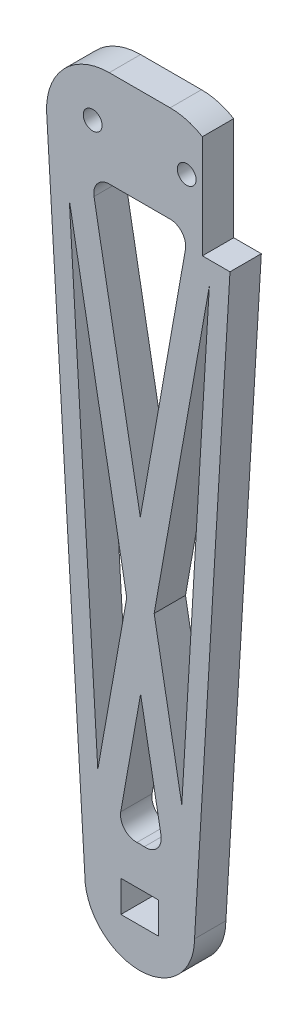
SolidWorks part; units mm, degrees
ref_plane "Front Plane" through (0, 0, 0) normal (0, 0, 1) x (1, 0, 0)
ref_plane "Top Plane" through (0, 0, 0) normal (0, 1, 0) x (1, 0, 0)
ref_plane "Right Plane" through (0, 0, 0) normal (1, 0, 0) x (0, 0, -1)
sketch "Sketch1" plane through (0, 0, 0) normal (0, 0, 1) x (1, 0, 0)
  line L0 (-30, 0) -> (30, 0)
  line L1 (0, 0) -> (15, 0)
  line L2 (55, 0) -> (-55, 0) construction
  line L3 (0, 0) -> (0, -210)
  line L4 (0, -44.7868) -> (0, 44.7868) construction
  line L5 (0, 0) -> (30, 0)
  line L6 (0, 0) -> (-30, 0)
  line L7 (0, 0) -> (-15, 0)
  line L8 (-6, -215) -> (6, -215)
  line L9 (-6, -215) -> (-6, -205)
  line L10 (-6, -205) -> (6, -205)
  line L11 (6, -215) -> (6, -205)
  line L12 (-6, -215) -> (6, -205) construction
  line L13 (-6, -205) -> (6, -215) construction
  line L14 (0, 0) -> (0, 15)
  line L15 (-30, 0) -> (-17.5, -210)
  line L16 (-30, 0) -> (30, 0)
  line L17 (-30, 0) -> (-30, 15.7704)
  line L18 (-30, 15.7704) -> (30, 15.7704)
  line L19 (30, 0) -> (30, 15.7704)
  line L20 (30, 0) -> (17.5, -210)
  circle A0 centre (15, 0) radius 3
  circle A1 centre (-15, 0) radius 3
  circle A2 centre (0, -210) radius 17.5
  point P4 (0, 0)
  dimension "D7" = 6
  dimension "D9" = 6
  dimension "D11" = 35
  dimension "D1" = 210
  dimension "D2" = 30
  dimension "D3" = 30
  dimension "D4" = 10
  dimension "D5" = 12
  dimension "D6" = 15
  dimension "D8" = 15
  dimension "D10" = 15
extrude "Boss-Extrude2" add sketch "Sketch1" along normal blind 10
fillet "Fillet1" radius 20 1 edges at (-30, 15.7704, 5)
fillet "Fillet2" radius 20 1 edges at (30, 15.7704, 5)
sketch "Sketch4" plane through (0, 0, 10) normal (0, 0, 1) x (1, 0, 0)
  line L0 (-29.3398, -11.0918) -> (-23.3398, -11.0918)
  line L1 (-29.6775, -5.418) -> (-17.5, -210) construction
  line L2 (29.3911, -10.23) -> (23.3911, -10.23)
  line L3 (29.6775, -5.418) -> (17.5, -210) construction
  line L4 (-18.3824, -195.1758) -> (-12.3824, -195.1758)
  line L5 (18.3824, -195.1758) -> (12.3824, -195.1758)
  line L6 (-12.3824, -195.1758) -> (-23.5439, -7.6624)
  line L7 (23.3911, -7.6624) -> (11.6198, -205.4193)
  line L8 (-22.9543, -15) -> (22.9543, -15)
  line L9 (-8.4362, -200.1287) -> (-16.4545, -196.0413)
  line L10 (9.2183, -200.015) -> (17.2308, -195.9163)
  line L11 (9.2183, -200.015) -> (-24.5465, -14.245)
  line L12 (17.2308, -195.9163) -> (-16.534, -10.1463)
  line L13 (-24.5465, -14.245) -> (-16.534, -10.1463)
  line L14 (-8.4362, -200.1287) -> (24.4903, -14.4152)
  line L15 (-16.4545, -196.0413) -> (16.472, -10.3277)
  line L16 (24.4903, -14.4152) -> (16.472, -10.3277)
  circle A0 centre (0, -210) radius 17.5
  circle A1 centre (15, 0) radius 15
  point P25 (0, -15)
  dimension "D5" = 15
  dimension "D1" = 6
  dimension "D2" = 6
  dimension "D3" = 6
  dimension "D4" = 6
  dimension "D6" = 9
  dimension "D7" = 9
extrude "Cut-Extrude1" cut sketch "Sketch4" against normal blind 10 contours L12 L15 L8 | L6 L15 L11 | L14 L12 L7 | A0 L11 L14
fillet "Fillet3" radius 5 4 edges at (8.2256, -194.5537, 5) (-7.3724, -194.1287, 5) (-15.6518, -15, 5) (15.6436, -15, 5)
sketch "Sketch5" plane through (0, 0, 10) normal (0, 0, 1) x (1, 0, 0)
  line L0 (15, 0) -> (30, 0)
  line L1 (55, 0) -> (-55, 0) construction
  line L2 (30, 0) -> (30, -20)
  line L3 (0, -175.7959) -> (34.2041, -175.7959)
  line L5 (30, -20) -> (30, 0)
  line L8 (0, -175.7959) -> (-19.536, -175.7959)
  line L9 (-29.6775, -5.418) -> (-17.5, -210) construction
  line L12 (30, 0) -> (20, 0)
  line L17 (30, 0) -> (30, 24.03)
  line L18 (30, 24.03) -> (20, 24.03)
  line L19 (20, 0) -> (20, 24.03)
  line L20 (30, 0) -> (20, 0)
  line L21 (30, 0) -> (30, -20)
  line L22 (30, -20) -> (20, -20)
  line L23 (20, 0) -> (20, -20)
  circle A0 centre (0, -210) radius 30
  circle A1 centre (0, -210) radius 34.2041
  circle A2 centre (0, -210) radius 36
  line M1 (17.5, -210) -> (29.6775, -5.418)
  arc M2 (29.6775, -5.418) -> (9.7128, 15.7704) centre (9.7128, -4.2296) ccw
  dimension "D3" = 60
  dimension "D4" = 36
  dimension "D1" = 15
  dimension "D2" = 20
  dimension "D5" = 24.03
  dimension "D6" = 10
  dimension "D7" = 20
  dimension "D8" = 10
extrude "Cut-Extrude6" cut sketch "Sketch5" against normal blind 10 contours L0 L23 L22 M1 M2 | L19 L0 M2
